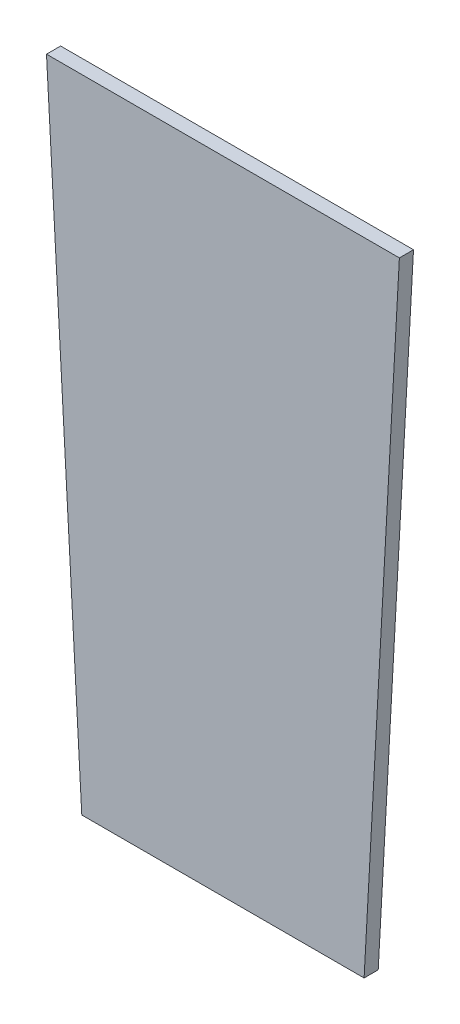
SolidWorks part; units mm, degrees
ref_plane "Płaszczyzna przednia" through (0, 0, 0) normal (0, 0, 1) x (1, 0, 0)
ref_plane "Płaszczyzna górna" through (0, 0, 0) normal (0, 1, 0) x (1, 0, 0)
ref_plane "Płaszczyzna prawa" through (0, 0, 0) normal (1, 0, 0) x (0, 0, -1)
sketch "Szkic1" plane through (0, 0, 0) normal (0, 0, 1) x (1, 0, 0)
  line L0 (-125, 249.5829) -> (125, 249.5829)
  line L1 (125, 249.5829) -> (100, -204.7297)
  line L2 (100, -204.7297) -> (-100, -204.7297)
  line L3 (-100, -204.7297) -> (-125, 249.5829)
  point P2 (0, 249.5829)
  point P5 (0, -204.7297)
  dimension "D1" = 250
  dimension "D2" = 200
  dimension "D3" = 455
extrude "Dodanie-wyciągnięcie1" add sketch "Szkic1" along normal blind 10
